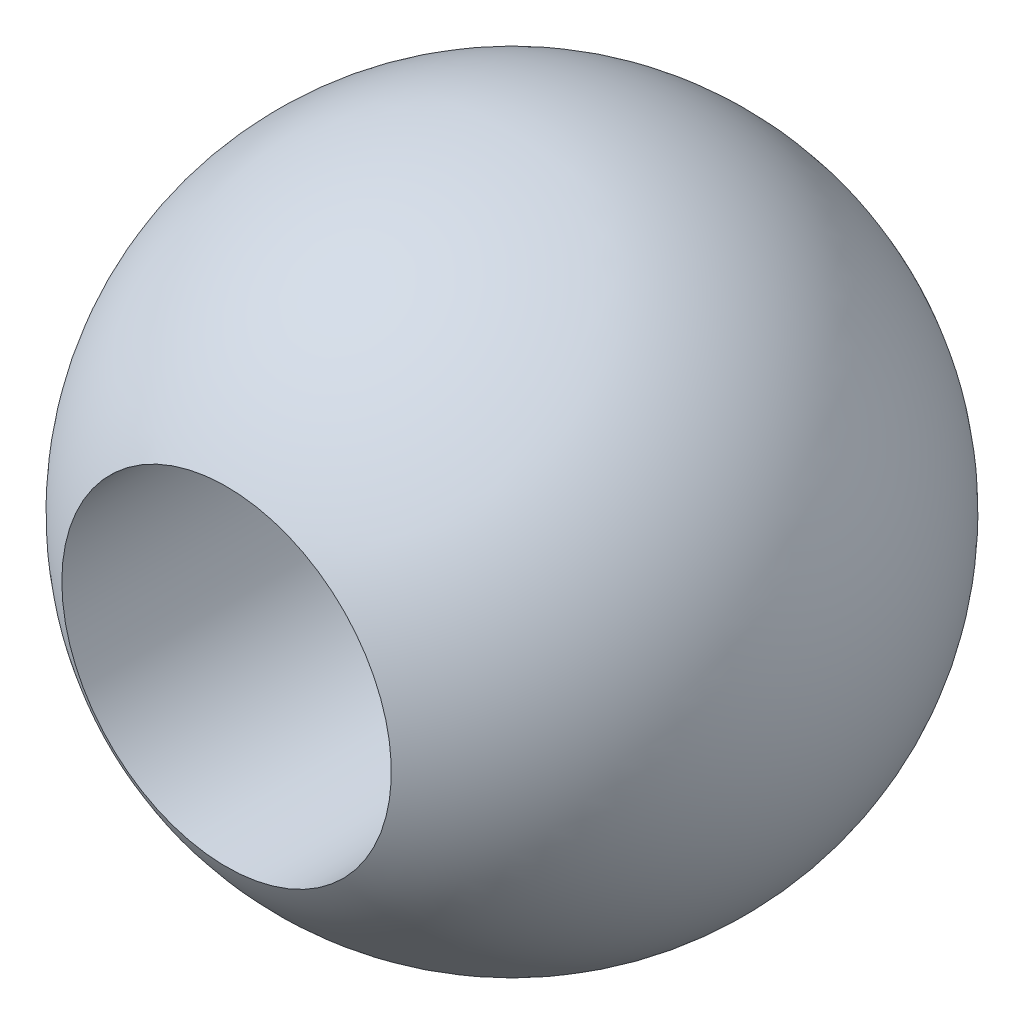
SolidWorks part; units mm, degrees
ref_plane "前视基准面" through (0, 0, 0) normal (0, 0, 1) x (1, 0, 0)
ref_plane "上视基准面" through (0, 0, 0) normal (0, 1, 0) x (1, 0, 0)
ref_plane "右视基准面" through (0, 0, 0) normal (1, 0, 0) x (0, 0, -1)
other "Configuration Table"
sketch "草图1" plane through (0, 0, 0) normal (0, 0, 1) x (1, 0, 0)
  line L0 (0, 4) -> (0, -4)
  arc A1 (0, -4) -> (0, 4) centre (0, 0) ccw
  dimension "D1" = 4
  dimension "D2" = 8
revolve "旋转1" add sketch "草图1" angle 360 about L0
sketch "草图2" plane through (0, 0, 0) normal (0, 0, 1) x (1, 0, 0)
  circle A0 centre (0, 0) radius 2
  dimension "D1" = 4
extrude "切除-拉伸1" cut sketch "草图2" against normal through all both and the other way through all
